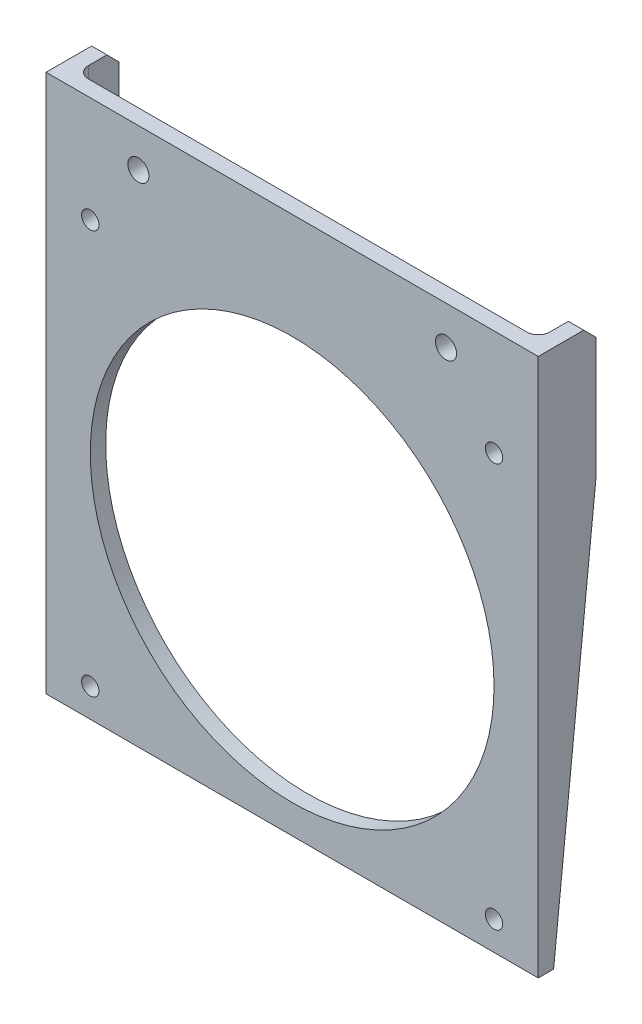
SolidWorks part; units mm, degrees
material "PLA"
ref_plane "Front Plane" through (0, 0, 0) normal (0, 0, 1) x (1, 0, 0)
ref_plane "Top Plane" through (0, 0, 0) normal (0, 1, 0) x (1, 0, 0)
ref_plane "Right Plane" through (0, 0, 0) normal (1, 0, 0) x (0, 0, -1)
sketch "Sketch1" plane through (0, 0, 0) normal (0, 0, 1) x (1, 0, 0)
  line L0 (0, 60) -> (120, 60) construction
  line L1 (0, 0) -> (120, 0)
  line L2 (0, 0) -> (0, 140)
  line L3 (0, 140) -> (120, 140)
  line L4 (120, 0) -> (120, 140)
  circle A0 centre (60, 60) radius 52.5
  dimension "D4" = 105
  dimension "D1" = 120
  dimension "D2" = 140
  dimension "D3" = 60
extrude "Boss-Extrude1" add sketch "Sketch1" along normal blind 4
sketch "Sketch2" plane through (0, 0, 4) normal (0, 0, 1) x (1, 0, 0)
  line L1 (7.5, 7.5) -> (112.5, 7.5) construction
  line L2 (7.5, 7.5) -> (7.5, 112.5) construction
  line L3 (7.5, 112.5) -> (112.5, 112.5) construction
  line L4 (112.5, 7.5) -> (112.5, 112.5) construction
  line L5 (7.5, 7.5) -> (112.5, 112.5) construction
  line L6 (7.5, 112.5) -> (112.5, 7.5) construction
  point P0 (60, 60)
  point P7 (7.5, 112.5)
  point P8 (112.5, 112.5)
  point P9 (112.5, 7.5)
  point P10 (7.5, 7.5)
  dimension "D1" = 105
hole_wizard "M4 Clearance Hole1" positions "Sketch2" profile "Sketch3" hole size "M4" standard "ANSI Metric" end condition through all
sketch "Sketch3" plane through (7.5, 7.5, 4) normal (1, 0, 0) x (0, -1, 0)
  line L0 (0, 0) -> (0, 4)
  line L1 (0, 4) -> (2.25, 4)
  line L2 (2.25, 4) -> (2.25, 0)
  line L5 (2.25, 0) -> (0, 0)
  line L11 (0, -6.35) -> (0, 107.95) construction
  dimension "Thru Hole Dia." = 4.5
  dimension "Thru Hole Depth" = 4
sketch "Sketch4" plane through (0, 0, 4) normal (0, 0, 1) x (1, 0, 0)
  line L0 (0, 130) -> (20, 130) construction
  line L1 (0, 140) -> (0, 0) construction
  line L2 (20, 130) -> (100, 130) construction
  line L3 (100, 130) -> (120, 130) construction
  line L4 (120, 0) -> (120, 140) construction
  line L5 (120, 140) -> (0, 140) construction
  point P11 (20, 130)
  point P12 (100, 130)
  dimension "D1" = 10
  dimension "D2" = 80
hole_wizard "M5 Clearance Hole1" positions "Sketch4" profile "Sketch5" hole size "M5" standard "ANSI Metric" end condition through all
sketch "Sketch5" plane through (100, 130, 4) normal (1, 0, 0) x (0, -1, 0)
  line L0 (0, 0) -> (0, 4)
  line L1 (0, 4) -> (2.75, 4)
  line L2 (2.75, 4) -> (2.75, 0)
  line L5 (2.75, 0) -> (0, 0)
  line L11 (0, -6.35) -> (0, 107.95) construction
  dimension "Thru Hole Dia." = 5.5
  dimension "Thru Hole Depth" = 4
ref_plane "Plane1" through (60, 0, 0) normal (-1, 0, 0) x (0, 0, 1)
sketch "Sketch6" plane through (120, 0, 0) normal (1, 0, 0) x (0, 0, -1)
  line L0 (-4, 140) -> (7.8291, 140)
  line L1 (7.8291, 140) -> (11, 136.8291)
  line L2 (11, 136.8291) -> (11, 105)
  line L3 (11, 105) -> (0, 0)
  line L4 (0, 0) -> (-4, 0)
  line L5 (-4, 0) -> (-4, 140)
  line L6 (-4, 0) -> (-4, 140) construction
  line L7 (-4, 0) -> (0, 0) construction
  dimension "D1" = 45
  dimension "D2" = 35
  dimension "D3" = 15
extrude "Boss-Extrude2" add sketch "Sketch6" along normal blind 4
mirror "Mirror1" about plane through (60, 0, 0) normal (-1, 0, 0) of "Boss-Extrude2"
fillet "Fillet1" radius 3 2 edges at (120, 70, 0) (0, 70, 0)
